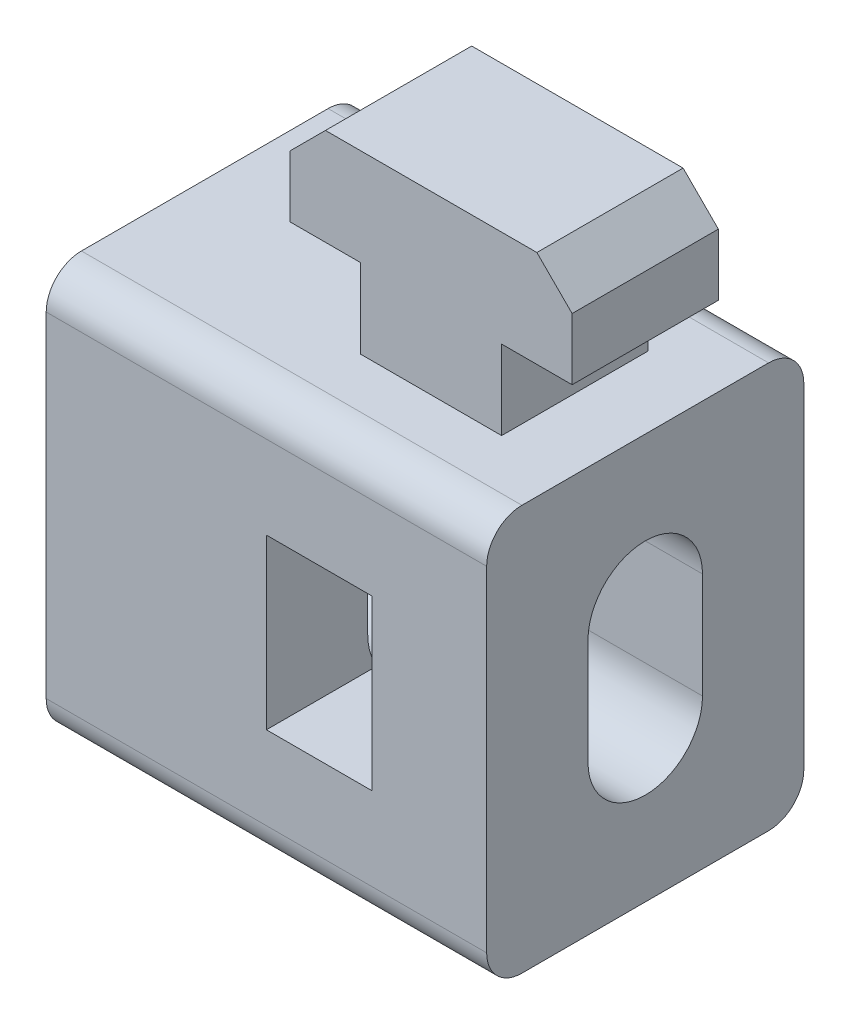
SolidWorks part; units mm, degrees
ref_plane "前视基准面" through (0, 0, 0) normal (0, 0, 1) x (1, 0, 0)
ref_plane "上视基准面" through (0, 0, 0) normal (0, 1, 0) x (1, 0, 0)
ref_plane "右视基准面" through (0, 0, 0) normal (1, 0, 0) x (0, 0, -1)
sketch "草图1" plane through (0, 0, 0) normal (0, 0, 1) x (1, 0, 0)
  line B0 (-14, 33) -> (-2, 33)
  line B1 (-16, 31) -> (-16, 27.5)
  line B2 (0, 31) -> (0, 27.5)
  line B3 (-16, 27.5) -> (-12, 27.5)
  line B4 (-4, 27.5) -> (0, 27.5)
  line B5 (-16, 31) -> (-14, 33)
  line B6 (0, 31) -> (-2, 33)
  line B7 (-12, 27.5) -> (-12, 23)
  line B8 (-4, 27.5) -> (-4, 23)
  line B9 (0, 0) -> (-25, 0)
  line B10 (-25, 23) -> (-12, 23)
  line B11 (-4, 23) -> (0, 23)
  line B12 (0, 23) -> (0, 0)
  line B13 (-25, 23) -> (-25, 0)
sketch_block_instance "A$C2EF8244A-1"
sketch_block "A$C2EF8244A"
extrude "凸台-拉伸1" add sketch "草图1" along normal mid plane 18
sketch "草图3" plane through (0, 33, 0) normal (0, 1, 0) x (1, 0, 0)
  line L1 (-19.1095, 4.15) -> (0, 4.15)
  line L2 (-19.1095, 4.15) -> (-19.1095, 12.0006)
  line L3 (-19.1095, 12.0006) -> (0, 12.0006)
  line L4 (0, 4.15) -> (0, 12.0006)
  line L5 (-19.1095, -4.15) -> (2.5373, -4.15)
  line L6 (-19.1095, -4.15) -> (-19.1095, -14.0787)
  line L7 (-19.1095, -14.0787) -> (2.5373, -14.0787)
  line L8 (2.5373, -4.15) -> (2.5373, -14.0787)
  dimension "D1" = 4.15
  dimension "D2" = 4.15
extrude "切除-拉伸1" cut sketch "草图3" against normal up to surface (10 mm away) up to face at (-18.5, 23, 0)
sketch "草图4" plane through (0, 0, 0) normal (1, 0, 0) x (0, 0, -1)
  line L0 (0, 8.5) -> (0, 14.5) construction
  line L1 (-3.25, 8.5) -> (-3.25, 14.5)
  line L2 (3.25, 8.5) -> (3.25, 14.5)
  line L3 (-9, 23) -> (9, 23) construction
  line L4 (-9, 0) -> (9, 0) construction
  arc A0 (-3.25, 8.5) -> (3.25, 8.5) centre (0, 8.5) ccw
  arc A1 (3.25, 14.5) -> (-3.25, 14.5) centre (0, 14.5) ccw
  point P3 (0, 11.5)
  dimension "D2" = 8.5
  dimension "D3" = 8.5
  dimension "D1" = 6.5
extrude "切除-拉伸2" cut sketch "草图4" against normal through all
sketch "草图5" plane through (0, 0, 9) normal (0, 0, 1) x (1, 0, 0)
  line L0 (-25, 23) -> (-25, 0) construction
  line L1 (-12.5, 16.285) -> (-6.5, 16.285)
  line L2 (-12.5, 16.285) -> (-12.5, 6.715)
  line L3 (-12.5, 6.715) -> (-6.5, 6.715)
  line L4 (-6.5, 16.285) -> (-6.5, 6.715)
  line L5 (0, 23) -> (-25, 23) construction
  dimension "D1" = 12.5
  dimension "D2" = 6
  dimension "D3" = 9.57
  dimension "D4" = 6.715
extrude "切除-拉伸3" cut sketch "草图5" against normal blind 10
fillet "圆角1" radius 2 4 edges at (-12.5, 0, -9) (-12.5, 23, -9) (-12.5, 0, 9) (-12.5, 23, 9)
